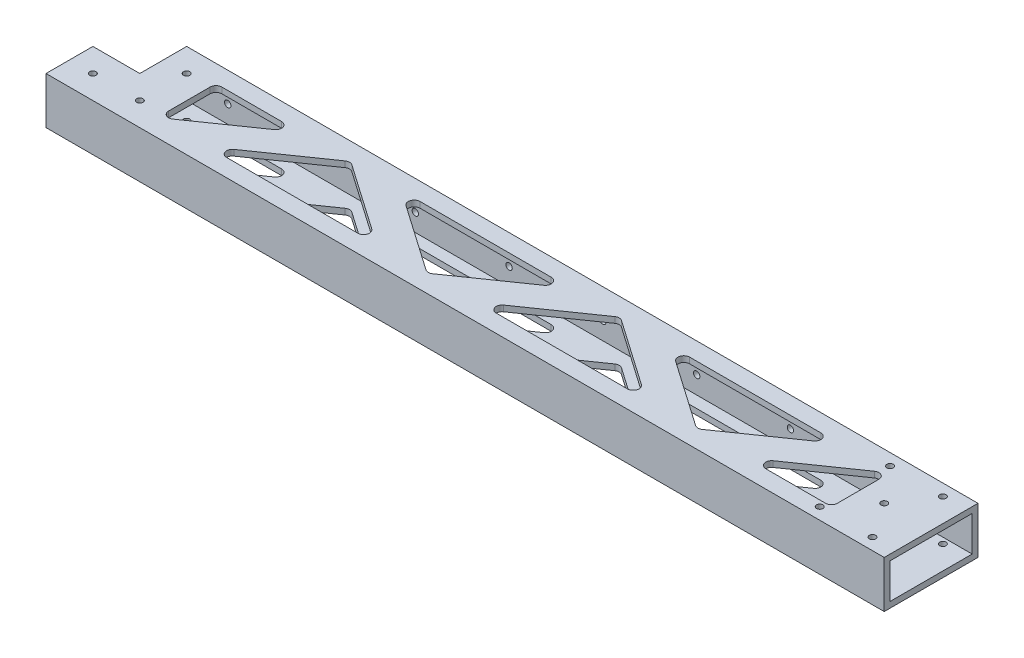
SolidWorks part; units mm, degrees
material "6061-T6 (SS)"
ref_plane "Front Plane" through (0, 0, 0) normal (0, 0, 1) x (1, 0, 0)
ref_plane "Top Plane" through (0, 0, 0) normal (0, 1, 0) x (1, 0, 0)
ref_plane "Right Plane" through (0, 0, 0) normal (1, 0, 0) x (0, 0, -1)
sketch "Sketch1" plane through (0, 0, 0) normal (1, 0, 0) x (0, 0, -1)
  line L0 (-22.225, 9.525) -> (-22.225, 12.7) construction
  line L1 (-25.4, -12.7) -> (25.4, -12.7)
  line L2 (-25.4, -12.7) -> (-25.4, 12.7)
  line L3 (-25.4, 12.7) -> (25.4, 12.7)
  line L4 (25.4, -12.7) -> (25.4, 12.7)
  line L5 (-25.4, -12.7) -> (25.4, 12.7) construction
  line L6 (-25.4, 12.7) -> (25.4, -12.7) construction
  line L7 (-22.225, -9.525) -> (22.225, -9.525)
  line L8 (-22.225, -9.525) -> (-22.225, 9.525)
  line L9 (-22.225, 9.525) -> (22.225, 9.525)
  line L10 (22.225, -9.525) -> (22.225, 9.525)
  line L11 (-22.225, -9.525) -> (22.225, 9.525) construction
  line L12 (-22.225, 9.525) -> (22.225, -9.525) construction
  line L13 (-22.225, 9.525) -> (-25.4, 9.525) construction
  point P0 (0, 0)
  point P6 (0, 0)
  dimension "D1" = 50.8
  dimension "D2" = 25.4
  dimension "D3" = 3.175
extrude "Boss-Extrude1" add sketch "Sketch1" along normal mid plane 454.025
sketch "Sketch2" plane through (0, -12.7, 0) normal (0, -1, 0) x (1, 0, 0)
  line L0 (-227.0125, 25.4) -> (-227.0125, -25.4) construction
  line L1 (-227.0125, -25.4) -> (-201.6125, -25.4)
  line L2 (-227.0125, -25.4) -> (-227.0125, 0)
  line L3 (-227.0125, 0) -> (-201.6125, 0)
  line L4 (-201.6125, -25.4) -> (-201.6125, 0)
  line L5 (227.0125, -25.4) -> (-227.0125, -25.4) construction
  dimension "D1" = 25.4
extrude "Cut-Extrude1" cut sketch "Sketch2" against normal through all
hole_wizard "#8-32 Tapped Hole1" positions "Sketch6" profile "Sketch5" tap size "#8-32" standard "ANSI Inch" end condition through all
sketch "Sketch6" plane through (0, -12.7, 0) normal (0, -1, 0) x (-1, 0, 0)
  line L0 (0, 0) -> (-50000, 0) construction
  line L1 (-227.0125, -25.4) -> (-227.0125, 25.4) construction
  line L2 (188.9125, 0) -> (188.9125, 50000) construction
  line L3 (201.6125, 25.4) -> (201.6125, 0) construction
  line L4 (201.6125, 0) -> (227.0125, 0) construction
  line L6 (214.3125, 0) -> (214.3125, 50000) construction
  line L7 (227.0125, -25.4) -> (227.0125, 0) construction
  line L8 (214.3125, -25.4) -> (214.3125, 0) construction
  line L10 (-227.0125, -25.4) -> (227.0125, -25.4) construction
  point P0 (-214.3125, 19.05)
  point P2 (-214.3125, -19.05)
  point P4 (-201.6125, 0)
  point P14 (188.9125, 12.7)
  point P16 (188.9125, -12.7)
  point P18 (214.3125, -12.7)
  point P31 (214.3125, 0)
  dimension "D1" = 38.1
  dimension "D2" = 12.7
  dimension "D3" = 25.4
  dimension "D4" = 12.7
sketch "Sketch5" plane through (214.3125, -12.7, -19.05) normal (1, 0, 0) x (0, 0, -1)
  line L0 (0, 0) -> (0, 25.4)
  line L1 (0, 25.4) -> (1.7272, 25.4)
  line L2 (1.7272, 25.4) -> (1.7272, 0)
  line L5 (1.7272, 0) -> (0, 0)
  line L11 (0, -6.35) -> (0, 107.95) construction
  dimension "Thru Tap Drill Dia." = 3.4544
  dimension "Thru Tap Drill Depth" = 25.4
cosmetic thread "Hole Thread1" parameters "D2"=4.1656
cosmetic thread "Hole Thread2" parameters "D2"=4.1656
cosmetic thread "Hole Thread3" parameters "D2"=4.1656
cosmetic thread "Hole Thread4" parameters "D2"=4.1656
cosmetic thread "Hole Thread5" parameters "D2"=4.1656
cosmetic thread "Hole Thread6" parameters "D2"=4.1656
sketch "Sketch7" plane through (0, 12.7, 0) normal (0, 1, 0) x (1, 0, 0)
  line L0 (227.0125, 25.4) -> (-201.6125, 25.4) construction
  line L1 (-176.2125, 25.4) -> (188.9125, 25.4) construction
  line L2 (-176.2125, 25.4) -> (-176.2125, -25.4) construction
  line L3 (-176.2125, -25.4) -> (188.9125, -25.4) construction
  line L4 (188.9125, 25.4) -> (188.9125, -25.4) construction
  line L5 (227.0125, -25.4) -> (-227.0125, -25.4) construction
  line L6 (-176.2125, -25.4) -> (-103.1875, 25.4) construction
  line L7 (-103.1875, 25.4) -> (-30.1625, -25.4) construction
  line L8 (-30.1625, -25.4) -> (42.8625, 25.4) construction
  line L9 (42.8625, 25.4) -> (115.8875, -25.4) construction
  line L10 (115.8875, -25.4) -> (188.9125, 25.4) construction
  line L11 (-176.2125, 15.875) -> (-130.5719, 15.875)
  line L12 (-130.5719, 15.875) -> (-176.2125, -15.875)
  line L13 (-176.2125, -15.875) -> (-176.2125, 15.875)
  line L14 (-148.8281, -15.875) -> (-103.1875, 15.875)
  line L15 (-103.1875, 15.875) -> (-57.5469, -15.875)
  line L16 (-57.5469, -15.875) -> (-148.8281, -15.875)
  line L17 (-75.8031, 15.875) -> (-30.1625, -15.875)
  line L18 (-30.1625, -15.875) -> (15.4781, 15.875)
  line L19 (15.4781, 15.875) -> (-75.8031, 15.875)
  line L20 (42.8625, 15.875) -> (88.5031, -15.875)
  line L21 (88.5031, -15.875) -> (-2.7781, -15.875)
  line L22 (-2.7781, -15.875) -> (42.8625, 15.875)
  line L23 (70.2469, 15.875) -> (161.5281, 15.875)
  line L24 (161.5281, 15.875) -> (115.8875, -15.875)
  line L25 (115.8875, -15.875) -> (70.2469, 15.875)
  line L26 (143.2719, -15.875) -> (188.9125, 15.875)
  line L27 (188.9125, 15.875) -> (188.9125, -15.875)
  line L28 (188.9125, -15.875) -> (143.2719, -15.875)
  line L29 (-80.3304, 15.875) -> (-50080.3304, 15.875) construction
  line L30 (-88.6845, -15.875) -> (49911.3155, -15.875) construction
  line L31 (-176.2125, -25.4) -> (-176.2125, -15.875) construction
  line L32 (-176.2125, 25.4) -> (-176.2125, 15.875) construction
  circle A0 centre (-188.9125, 12.7) radius 12.7 construction
  circle A1 centre (-188.9125, -12.7) radius 12.7 construction
  circle A2 centre (201.6125, 0) radius 12.7 construction
  dimension "D1" = 25.4
  dimension "D2" = 9.525
extrude "Cut-Extrude2" cut sketch "Sketch7" against normal through all
fillet "Fillet1" radius 3.175 36 edges at (-176.2125, 11.1125, -15.875) (-176.2125, -11.1125, -15.875) (-130.5719, 11.1125, -15.875) (-130.5719, -11.1125, -15.875) (-176.2125, -11.1125, 15.875) (-148.8281, -11.1125, 15.875) (-57.5469, 11.1125, 15.875) (-57.5469, -11.1125, 15.875) (-103.1875, 11.1125, -15.875) (-103.1875, -11.1125, -15.875) (-75.8031, -11.1125, -15.875) (-75.8031, 11.1125, -15.875) (15.4781, 11.1125, -15.875) (15.4781, -11.1125, -15.875) (-30.1625, 11.1125, 15.875) (-30.1625, -11.1125, 15.875) (42.8625, 11.1125, -15.875) (42.8625, -11.1125, -15.875) (-2.7781, -11.1125, 15.875) (88.5031, 11.1125, 15.875) (88.5031, -11.1125, 15.875) (70.2469, 11.1125, -15.875) (70.2469, -11.1125, -15.875) (161.5281, 11.1125, -15.875) (161.5281, -11.1125, -15.875) (188.9125, 11.1125, -15.875) (188.9125, -11.1125, -15.875) (143.2719, -11.1125, 15.875) (188.9125, 11.1125, 15.875) (188.9125, -11.1125, 15.875) (115.8875, -11.1125, 15.875) (115.8875, 11.1125, 15.875) (143.2719, 11.1125, 15.875) (-2.7781, 11.1125, 15.875) (-148.8281, 11.1125, 15.875) (-176.2125, 11.1125, 15.875)
hole_wizard "#8-32 Tapped Hole2" positions "Sketch9" profile "Sketch8" tap size "#8-32" standard "ANSI Inch"
sketch "Sketch9" plane through (0, 0, -25.4) normal (0, 0, -1) x (-1, 0, 0)
  line L0 (0, 0) -> (-50000, 0) construction
  line L1 (176.2125, 0) -> (125.4125, 0)
  line L2 (125.4125, 0) -> (74.6125, 0)
  line L3 (74.6125, 0) -> (23.8125, 0)
  line L4 (23.8125, 0) -> (-26.9875, 0)
  line L5 (-26.9875, 0) -> (-77.7875, 0)
  line L6 (-77.7875, 0) -> (-128.5875, 0)
  line L11 (-128.5875, 0) -> (-179.3875, 0)
  line L13 (201.6125, 12.7) -> (201.6125, -12.7) construction
  point P5 (176.2125, 0)
  point P7 (125.4125, 0)
  point P9 (74.6125, 0)
  point P11 (23.8125, 0)
  point P13 (-26.9875, 0)
  point P15 (-77.7875, 0)
  point P17 (-128.5875, 0)
  point P19 (-179.3875, 0)
  dimension "D1" = 50.8
  dimension "D2" = 25.4
sketch "Sketch8" plane through (-176.2125, 0, -25.4) normal (1, 0, 0) x (0, 1, 0)
  line L0 (0, 0) -> (0, 3.175)
  line L1 (0, 3.175) -> (1.7272, 3.175)
  line L2 (1.7272, 3.175) -> (1.7272, 0)
  line L5 (1.7272, 0) -> (0, 0)
  line L11 (0, -6.35) -> (0, 107.95) construction
  dimension "Thru Tap Drill Dia." = 3.4544
  dimension "Thru Tap Drill Depth" = 3.175
cosmetic thread "Hole Thread10" parameters "D2"=4.1656
cosmetic thread "Hole Thread11" parameters "D2"=4.1656
cosmetic thread "Hole Thread12" parameters "D2"=4.1656
cosmetic thread "Hole Thread13" parameters "D2"=4.1656
cosmetic thread "Hole Thread14" parameters "D2"=4.1656
cosmetic thread "Hole Thread15" parameters "D2"=4.1656
cosmetic thread "Hole Thread16" parameters "D2"=4.1656
cosmetic thread "Hole Thread17" parameters "D2"=4.1656
sketch "Sketch10" plane through (0, 0, -25.4) normal (0, 0, -1) x (-1, 0, 0)
  line L0 (-227.0125, 12.7) -> (201.6125, 12.7) construction
  line L1 (-142.6845, 12.7) -> (-91.8845, 12.7)
  line L2 (-142.6845, 12.7) -> (-142.6845, -0.5588)
  line L3 (-142.6845, -0.5588) -> (-91.8845, -0.5588)
  line L4 (-91.8845, 12.7) -> (-91.8845, -0.5588)
  line L5 (-227.0125, -12.7) -> (-227.0125, 12.7) construction
  line L6 (90.9955, 12.7) -> (141.7955, 12.7)
  line L7 (90.9955, 12.7) -> (90.9955, -0.5588)
  line L8 (90.9955, -0.5588) -> (141.7955, -0.5588)
  line L9 (141.7955, 12.7) -> (141.7955, -0.5588)
  line L10 (201.6125, 12.7) -> (201.6125, -12.7) construction
  dimension "D1" = 84.328
  dimension "D2" = 50.8
  dimension "D3" = 59.817
  dimension "D4" = 13.2588
extrude "Cut-Extrude3" [suppressed] cut sketch "Sketch10" against normal blind 12.7
hole_wizard "#8-32 Tapped Hole3" positions "Sketch12" profile "Sketch11" tap size "#8-32" standard "ANSI Inch" end condition through all
sketch "Sketch12" plane through (0, 12.7, 0) normal (0, 1, 0) x (1, 0, 0)
  line L0 (185.7375, 19.3534) -> (185.7375, -49980.6466) construction
  line L1 (227.0125, 0) -> (50227.0125, 0) construction
  line L2 (227.0125, 25.4) -> (227.0125, -25.4) construction
  point P0 (185.7375, 19.05)
  point P2 (185.7375, -19.05)
  point P11 (227.0125, 0)
  dimension "D1" = 41.275
  dimension "D2" = 38.1
sketch "Sketch11" plane through (185.7375, 12.7, -19.05) normal (1, 0, 0) x (0, 0, 1)
  line L0 (0, 0) -> (0, 25.4)
  line L1 (0, 25.4) -> (1.7272, 25.4)
  line L2 (1.7272, 25.4) -> (1.7272, 0)
  line L5 (1.7272, 0) -> (0, 0)
  line L11 (0, -6.35) -> (0, 107.95) construction
  dimension "Thru Tap Drill Dia." = 3.4544
  dimension "Thru Tap Drill Depth" = 25.4
cosmetic thread "Hole Thread18" parameters "D2"=4.1656
cosmetic thread "Hole Thread19" parameters "D2"=4.1656
